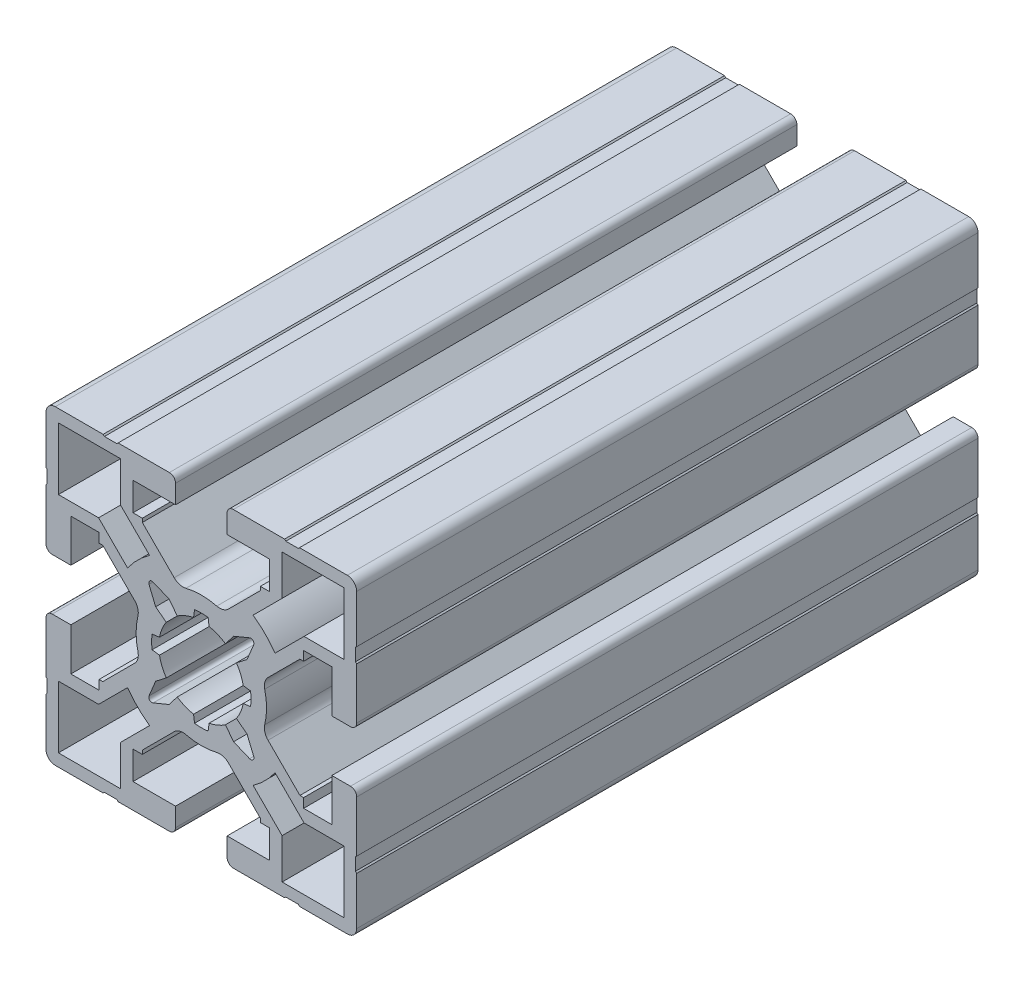
SolidWorks part; units mm, degrees
ref_plane "Plano frontal" through (0, 0, 0) normal (0, 0, 1) x (1, 0, 0)
ref_plane "Plano superior" through (0, 0, 0) normal (0, 1, 0) x (1, 0, 0)
ref_plane "Plano direito" through (0, 0, 0) normal (1, 0, 0) x (0, 0, -1)
sketch "Model" plane through (0, 0, 0) normal (0, 0, 1) x (1, 0, 0)
  line L64 (-23.5, -25) -> (-15.8, -25)
  line L65 (-15.8, -25) -> (-15.6, -24.8)
  line L66 (-15.6, -24.8) -> (-13.6, -24.8)
  line L67 (-13.6, -24.8) -> (-13.4, -25)
  line L68 (-13.4, -25) -> (-5.15, -25)
  line L69 (-4.15, -24) -> (-4.15, -21)
  line L70 (-4.15, -21) -> (-11, -21)
  line L71 (-11, -21) -> (-11, -16.464)
  line L72 (-11, -16.464) -> (-9.5, -16.464)
  line L73 (-9.5, -16.464) -> (-9.5, -15.864)
  line L74 (-9.5, -15.864) -> (-4.3679, -10.7318)
  line L75 (4.3679, -10.7318) -> (9.5, -15.864)
  line L76 (9.5, -15.864) -> (9.5, -16.464)
  line L77 (9.5, -16.464) -> (11, -16.464)
  line L78 (11, -16.464) -> (11, -21)
  line L79 (11, -21) -> (4.15, -21)
  line L80 (4.15, -21) -> (4.15, -24)
  line L81 (5.15, -25) -> (13.4, -25)
  line L82 (13.4, -25) -> (13.6, -24.8)
  line L83 (13.6, -24.8) -> (15.6, -24.8)
  line L84 (15.6, -24.8) -> (15.8, -25)
  line L85 (15.8, -25) -> (23.5, -25)
  line L86 (25, -23.5) -> (25, -15.8)
  line L87 (25, -15.8) -> (24.8, -15.6)
  line L88 (24.8, -15.6) -> (24.8, -13.6)
  line L89 (24.8, -13.6) -> (25, -13.4)
  line L90 (25, -13.4) -> (25, -5.15)
  line L91 (24, -4.15) -> (21, -4.15)
  line L92 (21, -4.15) -> (21, -11)
  line L93 (21, -11) -> (16.464, -11)
  line L94 (16.464, -11) -> (16.464, -9.5)
  line L95 (16.464, -9.5) -> (15.864, -9.5)
  line L96 (15.864, -9.5) -> (10.7318, -4.3679)
  line L97 (10.7318, 4.3679) -> (15.864, 9.5)
  line L98 (15.864, 9.5) -> (16.464, 9.5)
  line L99 (16.464, 9.5) -> (16.464, 11)
  line L100 (16.464, 11) -> (21, 11)
  line L101 (21, 11) -> (21, 4.15)
  line L102 (21, 4.15) -> (24, 4.15)
  line L103 (25, 5.15) -> (25, 13.4)
  line L104 (25, 13.4) -> (24.8, 13.6)
  line L105 (24.8, 13.6) -> (24.8, 15.6)
  line L106 (24.8, 15.6) -> (25, 15.8)
  line L107 (25, 15.8) -> (25, 23.5)
  line L108 (23.5, 25) -> (15.8, 25)
  line L109 (15.8, 25) -> (15.6, 24.8)
  line L110 (15.6, 24.8) -> (13.6, 24.8)
  line L111 (13.6, 24.8) -> (13.4, 25)
  line L112 (13.4, 25) -> (5.15, 25)
  line L113 (4.15, 24) -> (4.15, 21)
  line L114 (4.15, 21) -> (11, 21)
  line L115 (11, 21) -> (11, 16.464)
  line L116 (11, 16.464) -> (9.5, 16.464)
  line L117 (9.5, 16.464) -> (9.5, 15.864)
  line L118 (9.5, 15.864) -> (4.3679, 10.7318)
  line L119 (-4.3679, 10.7318) -> (-9.5, 15.864)
  line L120 (-9.5, 15.864) -> (-9.5, 16.464)
  line L121 (-9.5, 16.464) -> (-11, 16.464)
  line L122 (-11, 16.464) -> (-11, 21)
  line L123 (-11, 21) -> (-4.15, 21)
  line L124 (-4.15, 21) -> (-4.15, 24)
  line L125 (-5.15, 25) -> (-13.4, 25)
  line L126 (-13.4, 25) -> (-13.6, 24.8)
  line L127 (-13.6, 24.8) -> (-15.6, 24.8)
  line L128 (-15.6, 24.8) -> (-15.8, 25)
  line L129 (-15.8, 25) -> (-23.5, 25)
  line L130 (-25, 23.5) -> (-25, 15.8)
  line L131 (-25, 15.8) -> (-24.8, 15.6)
  line L132 (-24.8, 15.6) -> (-24.8, 13.6)
  line L133 (-24.8, 13.6) -> (-25, 13.4)
  line L134 (-25, 13.4) -> (-25, 5.15)
  line L135 (-24, 4.15) -> (-21, 4.15)
  line L136 (-21, 4.15) -> (-21, 11)
  line L137 (-21, 11) -> (-16.464, 11)
  line L138 (-16.464, 11) -> (-16.464, 9.5)
  line L139 (-16.464, 9.5) -> (-15.864, 9.5)
  line L140 (-15.864, 9.5) -> (-10.7318, 4.3679)
  line L141 (-10.7318, -4.3679) -> (-15.864, -9.5)
  line L142 (-15.864, -9.5) -> (-16.464, -9.5)
  line L143 (-16.464, -9.5) -> (-16.464, -11)
  line L144 (-16.464, -11) -> (-21, -11)
  line L145 (-21, -11) -> (-21, -4.15)
  line L146 (-21, -4.15) -> (-24, -4.15)
  line L147 (-25, -5.15) -> (-25, -13.4)
  line L148 (-25, -13.4) -> (-24.8, -13.6)
  line L149 (-24.8, -13.6) -> (-24.8, -15.6)
  line L150 (-24.8, -15.6) -> (-25, -15.8)
  line L151 (-25, -15.8) -> (-25, -23.5)
  line L152 (11.8673, 8.3317) -> (16.5355, 13)
  line L153 (16.5355, 13) -> (23, 13)
  line L154 (23, 13) -> (23, 23)
  line L155 (23, 23) -> (13, 23)
  line L156 (13, 23) -> (13, 16.5355)
  line L157 (13, 16.5355) -> (8.3317, 11.8673)
  line L158 (-13, 23) -> (-13, 16.5355)
  line L159 (-13, 16.5355) -> (-8.3317, 11.8673)
  line L160 (-11.8673, 8.3317) -> (-16.5355, 13)
  line L161 (-16.5355, 13) -> (-23, 13)
  line L162 (-23, 13) -> (-23, 23)
  line L163 (-23, 23) -> (-13, 23)
  line L164 (-13, -23) -> (-23, -23)
  line L165 (-23, -23) -> (-23, -13)
  line L166 (-23, -13) -> (-16.5355, -13)
  line L167 (-16.5355, -13) -> (-11.8673, -8.3317)
  line L168 (-8.3317, -11.8673) -> (-13, -16.5355)
  line L169 (-13, -16.5355) -> (-13, -23)
  line L170 (8.3317, -11.8673) -> (13, -16.5355)
  line L171 (13, -16.5355) -> (13, -23)
  line L172 (13, -23) -> (23, -23)
  line L173 (23, -23) -> (23, -13)
  line L174 (23, -13) -> (16.5355, -13)
  line L175 (16.5355, -13) -> (11.8673, -8.3317)
  line L176 (-7.7694, -8.4227) -> (-5.1887, -7.3537)
  line L177 (-5.1887, -7.3537) -> (-3.8785, -5.6462)
  line L178 (-1.25, -6.735) -> (-1.0933, -7.9249)
  line L179 (1.0933, -7.9249) -> (1.25, -6.735)
  line L180 (3.8785, -5.6462) -> (5.1887, -7.3537)
  line L181 (5.1887, -7.3537) -> (7.7694, -8.4227)
  line L182 (8.4227, -7.7694) -> (7.3537, -5.1887)
  line L183 (7.3537, -5.1887) -> (5.6462, -3.8785)
  line L184 (6.735, -1.25) -> (7.9249, -1.0933)
  line L185 (7.9249, 1.0933) -> (6.735, 1.25)
  line L186 (5.6462, 3.8785) -> (7.3537, 5.1887)
  line L187 (7.3537, 5.1887) -> (8.4227, 7.7694)
  line L188 (7.7694, 8.4227) -> (5.1887, 7.3537)
  line L189 (5.1887, 7.3537) -> (3.8785, 5.6462)
  line L190 (1.25, 6.735) -> (1.0933, 7.9249)
  line L191 (-1.0933, 7.9249) -> (-1.25, 6.735)
  line L192 (-3.8785, 5.6462) -> (-5.1887, 7.3537)
  line L193 (-5.1887, 7.3537) -> (-7.7694, 8.4227)
  line L194 (-8.4227, 7.7694) -> (-7.3537, 5.1887)
  line L195 (-7.3537, 5.1887) -> (-5.6462, 3.8785)
  line L196 (-6.735, 1.25) -> (-7.9249, 1.0933)
  line L197 (-7.9249, -1.0933) -> (-6.735, -1.25)
  line L198 (-5.6462, -3.8785) -> (-7.3537, -5.1887)
  line L199 (-7.3537, -5.1887) -> (-8.4227, -7.7694)
  line L342 (0, 8.8704) -> (0, 13.9613) construction
  line L343 (13.42, 0) -> (6.735, 0) construction
  line L345 (3.8417, 0) -> (-2.8013, 0) construction
  line L346 (-3.8827, 0) -> (-8.9809, 0) construction
  line L347 (-10.5, 0) -> (-14.388, 0) construction
  line L350 (0, -4.7052) -> (0, 6.735) construction
  line L351 (0, -12.2643) -> (0, -5.7851) construction
  arc A53 (-5.15, -25) -> (-4.15, -24) centre (-5.15, -24) ccw
  arc A54 (-2.4811, -10.2027) -> (-4.3679, -10.7318) centre (-2.9536, -12.146) ccw
  arc A55 (-2.4811, -10.2027) -> (2.4811, -10.2027) centre (0, 0) ccw
  arc A56 (4.3679, -10.7318) -> (2.4811, -10.2027) centre (2.9536, -12.146) ccw
  arc A57 (4.15, -24) -> (5.15, -25) centre (5.15, -24) ccw
  arc A58 (23.5, -25) -> (25, -23.5) centre (23.5, -23.5) ccw
  arc A59 (25, -5.15) -> (24, -4.15) centre (24, -5.15) ccw
  arc A60 (10.2027, -2.4811) -> (10.7318, -4.3679) centre (12.146, -2.9536) ccw
  arc A61 (10.2027, -2.4811) -> (10.2027, 2.4811) centre (0, 0) ccw
  arc A62 (10.7318, 4.3679) -> (10.2027, 2.4811) centre (12.146, 2.9536) ccw
  arc A63 (24, 4.15) -> (25, 5.15) centre (24, 5.15) ccw
  arc A64 (25, 23.5) -> (23.5, 25) centre (23.5, 23.5) ccw
  arc A65 (5.15, 25) -> (4.15, 24) centre (5.15, 24) ccw
  arc A66 (2.4811, 10.2027) -> (4.3679, 10.7318) centre (2.9536, 12.146) ccw
  arc A67 (2.4811, 10.2027) -> (-2.4811, 10.2027) centre (0, 0) ccw
  arc A68 (-4.3679, 10.7318) -> (-2.4811, 10.2027) centre (-2.9536, 12.146) ccw
  arc A69 (-4.15, 24) -> (-5.15, 25) centre (-5.15, 24) ccw
  arc A70 (-23.5, 25) -> (-25, 23.5) centre (-23.5, 23.5) ccw
  arc A71 (-25, 5.15) -> (-24, 4.15) centre (-24, 5.15) ccw
  arc A72 (-10.2027, 2.4811) -> (-10.7318, 4.3679) centre (-12.146, 2.9536) ccw
  arc A73 (-10.2027, 2.4811) -> (-10.2027, -2.4811) centre (0, 0) ccw
  arc A74 (-10.7318, -4.3679) -> (-10.2027, -2.4811) centre (-12.146, -2.9536) ccw
  arc A75 (-24, -4.15) -> (-25, -5.15) centre (-24, -5.15) ccw
  arc A76 (-25, -23.5) -> (-23.5, -25) centre (-23.5, -23.5) ccw
  arc A77 (11.8673, 8.3317) -> (8.3317, 11.8673) centre (0, 0) ccw
  arc A78 (-8.3317, 11.8673) -> (-11.8673, 8.3317) centre (0, 0) ccw
  arc A79 (-11.8673, -8.3317) -> (-8.3317, -11.8673) centre (0, 0) ccw
  arc A80 (8.3317, -11.8673) -> (11.8673, -8.3317) centre (0, 0) ccw
  arc A81 (-8.3143, -8.3143) -> (-7.7694, -8.4227) centre (-7.9608, -7.9608) ccw
  arc A82 (-3.8785, -5.6462) -> (-1.25, -6.735) centre (0, 0) ccw
  arc A83 (-1.0933, -7.9249) -> (1.0933, -7.9249) centre (0, 0) ccw
  arc A84 (1.25, -6.735) -> (3.8785, -5.6462) centre (0, 0) ccw
  arc A85 (7.7694, -8.4227) -> (8.4227, -7.7694) centre (7.9608, -7.9608) ccw
  arc A86 (5.6462, -3.8785) -> (6.735, -1.25) centre (0, 0) ccw
  arc A87 (7.9249, -1.0933) -> (7.9249, 1.0933) centre (0, 0) ccw
  arc A88 (6.735, 1.25) -> (5.6462, 3.8785) centre (0, 0) ccw
  arc A89 (8.4227, 7.7694) -> (7.7694, 8.4227) centre (7.9608, 7.9608) ccw
  arc A90 (3.8785, 5.6462) -> (1.25, 6.735) centre (0, 0) ccw
  arc A91 (1.0933, 7.9249) -> (-1.0933, 7.9249) centre (0, 0) ccw
  arc A92 (-1.25, 6.735) -> (-3.8785, 5.6462) centre (0, 0) ccw
  arc A93 (-7.7694, 8.4227) -> (-8.4227, 7.7694) centre (-7.9608, 7.9608) ccw
  arc A94 (-5.6462, 3.8785) -> (-6.735, 1.25) centre (0, 0) ccw
  arc A95 (-7.9249, 1.0933) -> (-7.9249, -1.0933) centre (0, 0) ccw
  arc A96 (-6.735, -1.25) -> (-5.6462, -3.8785) centre (0, 0) ccw
  arc A97 (-8.4227, -7.7694) -> (-8.3143, -8.3143) centre (-7.9608, -7.9608) ccw
extrude "Ressalto-extrusão1" add sketch "Model" along normal blind 500
sketch "Sketch1" plane through (0, 0, 500) normal (0, 0, 1) x (1, 0, 0)
  line L88 (-4.15, -24) -> (-4.15, -21)
  line L89 (-4.15, -21) -> (-11, -21)
  line L90 (-11, -21) -> (-11, -16.464)
  line L91 (-11, -16.464) -> (-9.5, -16.464)
  line L92 (-9.5, -16.464) -> (-9.5, -15.864)
  line L93 (-9.5, -15.864) -> (-4.3679, -10.7318)
  line L94 (4.3679, -10.7318) -> (9.5, -15.864)
  line L95 (9.5, -15.864) -> (9.5, -16.464)
  line L96 (9.5, -16.464) -> (11, -16.464)
  line L97 (11, -16.464) -> (11, -21)
  line L98 (11, -21) -> (4.15, -21)
  line L99 (4.15, -21) -> (4.15, -24)
  line L100 (5.15, -25) -> (13.4, -25)
  line L101 (13.4, -25) -> (13.6, -24.8)
  line L102 (13.6, -24.8) -> (15.6, -24.8)
  line L103 (15.6, -24.8) -> (15.8, -25)
  line L104 (15.8, -25) -> (23.5, -25)
  line L105 (25, -23.5) -> (25, -15.8)
  line L106 (25, -15.8) -> (24.8, -15.6)
  line L107 (24.8, -15.6) -> (24.8, -13.6)
  line L108 (24.8, -13.6) -> (25, -13.4)
  line L109 (25, -13.4) -> (25, -5.15)
  line L110 (24, -4.15) -> (21, -4.15)
  line L111 (21, -4.15) -> (21, -11)
  line L112 (21, -11) -> (16.464, -11)
  line L113 (16.464, -11) -> (16.464, -9.5)
  line L114 (16.464, -9.5) -> (15.864, -9.5)
  line L115 (15.864, -9.5) -> (10.7318, -4.3679)
  line L116 (10.7318, 4.3679) -> (15.864, 9.5)
  line L117 (15.864, 9.5) -> (16.464, 9.5)
  line L118 (16.464, 9.5) -> (16.464, 11)
  line L119 (16.464, 11) -> (21, 11)
  line L120 (21, 11) -> (21, 4.15)
  line L121 (21, 4.15) -> (24, 4.15)
  line L122 (25, 5.15) -> (25, 13.4)
  line L123 (25, 13.4) -> (24.8, 13.6)
  line L124 (24.8, 13.6) -> (24.8, 15.6)
  line L125 (24.8, 15.6) -> (25, 15.8)
  line L126 (25, 15.8) -> (25, 23.5)
  line L127 (23.5, 25) -> (15.8, 25)
  line L128 (15.8, 25) -> (15.6, 24.8)
  line L129 (15.6, 24.8) -> (13.6, 24.8)
  line L130 (13.6, 24.8) -> (13.4, 25)
  line L131 (13.4, 25) -> (5.15, 25)
  line L132 (4.15, 24) -> (4.15, 21)
  line L133 (4.15, 21) -> (11, 21)
  line L134 (11, 21) -> (11, 16.464)
  line L135 (11, 16.464) -> (9.5, 16.464)
  line L136 (9.5, 16.464) -> (9.5, 15.864)
  line L137 (9.5, 15.864) -> (4.3679, 10.7318)
  line L138 (-4.3679, 10.7318) -> (-9.5, 15.864)
  line L139 (-9.5, 15.864) -> (-9.5, 16.464)
  line L140 (-9.5, 16.464) -> (-11, 16.464)
  line L141 (-11, 16.464) -> (-11, 21)
  line L142 (-11, 21) -> (-4.15, 21)
  line L143 (-4.15, 21) -> (-4.15, 24)
  line L144 (-5.15, 25) -> (-13.4, 25)
  line L145 (-13.4, 25) -> (-13.6, 24.8)
  line L146 (-13.6, 24.8) -> (-15.6, 24.8)
  line L147 (-15.6, 24.8) -> (-15.8, 25)
  line L148 (-15.8, 25) -> (-23.5, 25)
  line L149 (-25, 23.5) -> (-25, 15.8)
  line L150 (-25, 15.8) -> (-24.8, 15.6)
  line L151 (-24.8, 15.6) -> (-24.8, 13.6)
  line L152 (-24.8, 13.6) -> (-25, 13.4)
  line L153 (-25, 13.4) -> (-25, 5.15)
  line L154 (-24, 4.15) -> (-21, 4.15)
  line L155 (-21, 4.15) -> (-21, 11)
  line L156 (-21, 11) -> (-16.464, 11)
  line L157 (-16.464, 11) -> (-16.464, 9.5)
  line L158 (-16.464, 9.5) -> (-15.864, 9.5)
  line L159 (-15.864, 9.5) -> (-10.7318, 4.3679)
  line L160 (-10.7318, -4.3679) -> (-15.864, -9.5)
  line L161 (-15.864, -9.5) -> (-16.464, -9.5)
  line L162 (-16.464, -9.5) -> (-16.464, -11)
  line L163 (-16.464, -11) -> (-21, -11)
  line L164 (-21, -11) -> (-21, -4.15)
  line L165 (-21, -4.15) -> (-24, -4.15)
  line L166 (-25, -5.15) -> (-25, -13.4)
  line L167 (-25, -13.4) -> (-24.8, -13.6)
  line L168 (-24.8, -13.6) -> (-24.8, -15.6)
  line L169 (-24.8, -15.6) -> (-25, -15.8)
  line L170 (-25, -15.8) -> (-25, -23.5)
  line L171 (-23.5, -25) -> (-15.8, -25)
  line L172 (-15.8, -25) -> (-15.6, -24.8)
  line L173 (-15.6, -24.8) -> (-13.6, -24.8)
  line L174 (-13.6, -24.8) -> (-13.4, -25)
  line L175 (-13.4, -25) -> (-5.15, -25)
  line L176 (-4.15, -24) -> (-4.15, -21)
  line L177 (-4.15, -21) -> (-11, -21)
  line L178 (-11, -21) -> (-11, -16.464)
  line L179 (-11, -16.464) -> (-9.5, -16.464)
  line L180 (-9.5, -16.464) -> (-9.5, -15.864)
  line L181 (-9.5, -15.864) -> (-4.3679, -10.7318)
  line L182 (4.3679, -10.7318) -> (9.5, -15.864)
  line L183 (9.5, -15.864) -> (9.5, -16.464)
  line L184 (9.5, -16.464) -> (11, -16.464)
  line L185 (11, -16.464) -> (11, -21)
  line L186 (11, -21) -> (4.15, -21)
  line L187 (4.15, -21) -> (4.15, -24)
  line L188 (5.15, -25) -> (13.4, -25)
  line L189 (13.4, -25) -> (13.6, -24.8)
  line L190 (13.6, -24.8) -> (15.6, -24.8)
  line L191 (15.6, -24.8) -> (15.8, -25)
  line L192 (15.8, -25) -> (23.5, -25)
  line L193 (25, -23.5) -> (25, -15.8)
  line L194 (25, -15.8) -> (24.8, -15.6)
  line L195 (24.8, -15.6) -> (24.8, -13.6)
  line L196 (24.8, -13.6) -> (25, -13.4)
  line L197 (25, -13.4) -> (25, -5.15)
  line L198 (24, -4.15) -> (21, -4.15)
  line L199 (21, -4.15) -> (21, -11)
  line L200 (21, -11) -> (16.464, -11)
  line L201 (16.464, -11) -> (16.464, -9.5)
  line L202 (16.464, -9.5) -> (15.864, -9.5)
  line L203 (15.864, -9.5) -> (10.7318, -4.3679)
  line L204 (10.7318, 4.3679) -> (15.864, 9.5)
  line L205 (15.864, 9.5) -> (16.464, 9.5)
  line L206 (16.464, 9.5) -> (16.464, 11)
  line L207 (16.464, 11) -> (21, 11)
  line L208 (21, 11) -> (21, 4.15)
  line L209 (21, 4.15) -> (24, 4.15)
  line L210 (25, 5.15) -> (25, 13.4)
  line L211 (25, 13.4) -> (24.8, 13.6)
  line L212 (24.8, 13.6) -> (24.8, 15.6)
  line L213 (24.8, 15.6) -> (25, 15.8)
  line L214 (25, 15.8) -> (25, 23.5)
  line L215 (23.5, 25) -> (15.8, 25)
  line L216 (15.8, 25) -> (15.6, 24.8)
  line L217 (15.6, 24.8) -> (13.6, 24.8)
  line L218 (13.6, 24.8) -> (13.4, 25)
  line L219 (13.4, 25) -> (5.15, 25)
  line L220 (4.15, 24) -> (4.15, 21)
  line L221 (4.15, 21) -> (11, 21)
  line L222 (11, 21) -> (11, 16.464)
  line L223 (11, 16.464) -> (9.5, 16.464)
  line L224 (9.5, 16.464) -> (9.5, 15.864)
  line L225 (9.5, 15.864) -> (4.3679, 10.7318)
  line L226 (-4.3679, 10.7318) -> (-9.5, 15.864)
  line L227 (-9.5, 15.864) -> (-9.5, 16.464)
  line L228 (-9.5, 16.464) -> (-11, 16.464)
  line L229 (-11, 16.464) -> (-11, 21)
  line L230 (-11, 21) -> (-4.15, 21)
  line L231 (-4.15, 21) -> (-4.15, 24)
  line L232 (-5.15, 25) -> (-13.4, 25)
  line L233 (-13.4, 25) -> (-13.6, 24.8)
  line L234 (-13.6, 24.8) -> (-15.6, 24.8)
  line L235 (-15.6, 24.8) -> (-15.8, 25)
  line L236 (-15.8, 25) -> (-23.5, 25)
  line L237 (-25, 23.5) -> (-25, 15.8)
  line L238 (-25, 15.8) -> (-24.8, 15.6)
  line L239 (-24.8, 15.6) -> (-24.8, 13.6)
  line L240 (-24.8, 13.6) -> (-25, 13.4)
  line L241 (-25, 13.4) -> (-25, 5.15)
  line L242 (-24, 4.15) -> (-21, 4.15)
  line L243 (-21, 4.15) -> (-21, 11)
  line L244 (-21, 11) -> (-16.464, 11)
  line L245 (-16.464, 11) -> (-16.464, 9.5)
  line L246 (-16.464, 9.5) -> (-15.864, 9.5)
  line L247 (-15.864, 9.5) -> (-10.7318, 4.3679)
  line L248 (-10.7318, -4.3679) -> (-15.864, -9.5)
  line L249 (-15.864, -9.5) -> (-16.464, -9.5)
  line L250 (-16.464, -9.5) -> (-16.464, -11)
  line L251 (-16.464, -11) -> (-21, -11)
  line L252 (-21, -11) -> (-21, -4.15)
  line L253 (-21, -4.15) -> (-24, -4.15)
  line L254 (-25, -5.15) -> (-25, -13.4)
  line L255 (-25, -13.4) -> (-24.8, -13.6)
  line L256 (-24.8, -13.6) -> (-24.8, -15.6)
  line L257 (-24.8, -15.6) -> (-25, -15.8)
  line L258 (-25, -15.8) -> (-25, -23.5)
  line L259 (-23.5, -25) -> (-15.8, -25)
  line L260 (-15.8, -25) -> (-15.6, -24.8)
  line L261 (-15.6, -24.8) -> (-13.6, -24.8)
  line L262 (-13.6, -24.8) -> (-13.4, -25)
  line L263 (-13.4, -25) -> (-5.15, -25)
  arc A24 (-5.15, -25) -> (-4.15, -24) centre (-5.15, -24) ccw
  arc A25 (-2.4811, -10.2027) -> (-4.3679, -10.7318) centre (-2.9536, -12.146) ccw
  arc A26 (-2.4811, -10.2027) -> (2.4811, -10.2027) centre (0, 0) ccw
  arc A27 (4.3679, -10.7318) -> (2.4811, -10.2027) centre (2.9536, -12.146) ccw
  arc A28 (4.15, -24) -> (5.15, -25) centre (5.15, -24) ccw
  arc A29 (23.5, -25) -> (25, -23.5) centre (23.5, -23.5) ccw
  arc A30 (25, -5.15) -> (24, -4.15) centre (24, -5.15) ccw
  arc A31 (10.2027, -2.4811) -> (10.7318, -4.3679) centre (12.146, -2.9536) ccw
  arc A32 (10.2027, -2.4811) -> (10.2027, 2.4811) centre (0, 0) ccw
  arc A33 (10.7318, 4.3679) -> (10.2027, 2.4811) centre (12.146, 2.9536) ccw
  arc A34 (24, 4.15) -> (25, 5.15) centre (24, 5.15) ccw
  arc A35 (25, 23.5) -> (23.5, 25) centre (23.5, 23.5) ccw
  arc A36 (5.15, 25) -> (4.15, 24) centre (5.15, 24) ccw
  arc A37 (2.4811, 10.2027) -> (4.3679, 10.7318) centre (2.9536, 12.146) ccw
  arc A38 (2.4811, 10.2027) -> (-2.4811, 10.2027) centre (0, 0) ccw
  arc A39 (-4.3679, 10.7318) -> (-2.4811, 10.2027) centre (-2.9536, 12.146) ccw
  arc A40 (-4.15, 24) -> (-5.15, 25) centre (-5.15, 24) ccw
  arc A41 (-23.5, 25) -> (-25, 23.5) centre (-23.5, 23.5) ccw
  arc A42 (-25, 5.15) -> (-24, 4.15) centre (-24, 5.15) ccw
  arc A43 (-10.2027, 2.4811) -> (-10.7318, 4.3679) centre (-12.146, 2.9536) ccw
  arc A44 (-10.2027, 2.4811) -> (-10.2027, -2.4811) centre (0, 0) ccw
  arc A45 (-10.7318, -4.3679) -> (-10.2027, -2.4811) centre (-12.146, -2.9536) ccw
  arc A46 (-24, -4.15) -> (-25, -5.15) centre (-24, -5.15) ccw
  arc A47 (-25, -23.5) -> (-23.5, -25) centre (-23.5, -23.5) ccw
  arc A48 (-5.15, -25) -> (-4.15, -24) centre (-5.15, -24) ccw
  arc A49 (-2.4811, -10.2027) -> (-4.3679, -10.7318) centre (-2.9536, -12.146) ccw
  arc A50 (-2.4811, -10.2027) -> (2.4811, -10.2027) centre (0, 0) ccw
  arc A51 (4.3679, -10.7318) -> (2.4811, -10.2027) centre (2.9536, -12.146) ccw
  arc A52 (4.15, -24) -> (5.15, -25) centre (5.15, -24) ccw
  arc A53 (23.5, -25) -> (25, -23.5) centre (23.5, -23.5) ccw
  arc A54 (25, -5.15) -> (24, -4.15) centre (24, -5.15) ccw
  arc A55 (10.2027, -2.4811) -> (10.7318, -4.3679) centre (12.146, -2.9536) ccw
  arc A56 (10.2027, -2.4811) -> (10.2027, 2.4811) centre (0, 0) ccw
  arc A57 (10.7318, 4.3679) -> (10.2027, 2.4811) centre (12.146, 2.9536) ccw
  arc A58 (24, 4.15) -> (25, 5.15) centre (24, 5.15) ccw
  arc A59 (25, 23.5) -> (23.5, 25) centre (23.5, 23.5) ccw
  arc A60 (5.15, 25) -> (4.15, 24) centre (5.15, 24) ccw
  arc A61 (2.4811, 10.2027) -> (4.3679, 10.7318) centre (2.9536, 12.146) ccw
  arc A62 (2.4811, 10.2027) -> (-2.4811, 10.2027) centre (0, 0) ccw
  arc A63 (-4.3679, 10.7318) -> (-2.4811, 10.2027) centre (-2.9536, 12.146) ccw
  arc A64 (-4.15, 24) -> (-5.15, 25) centre (-5.15, 24) ccw
  arc A65 (-23.5, 25) -> (-25, 23.5) centre (-23.5, 23.5) ccw
  arc A66 (-25, 5.15) -> (-24, 4.15) centre (-24, 5.15) ccw
  arc A67 (-10.2027, 2.4811) -> (-10.7318, 4.3679) centre (-12.146, 2.9536) ccw
  arc A68 (-10.2027, 2.4811) -> (-10.2027, -2.4811) centre (0, 0) ccw
  arc A69 (-10.7318, -4.3679) -> (-10.2027, -2.4811) centre (-12.146, -2.9536) ccw
  arc A70 (-24, -4.15) -> (-25, -5.15) centre (-24, -5.15) ccw
  arc A71 (-25, -23.5) -> (-23.5, -25) centre (-23.5, -23.5) ccw
  dimension "D1" = 0
extrude "Cut-Extrude1" cut sketch "Sketch1" against normal blind 400
